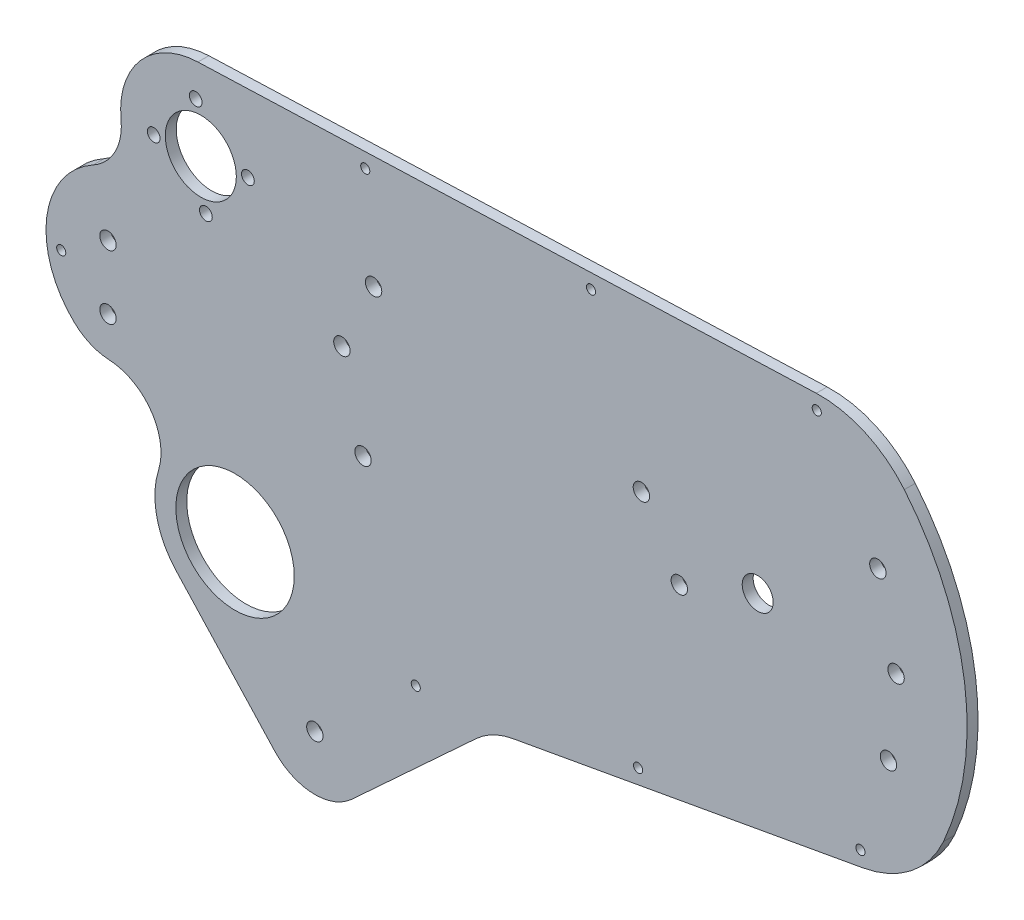
SolidWorks part; units mm, degrees
ref_plane "Front Plane" through (0, 0, 0) normal (0, 0, 1) x (1, 0, 0)
ref_plane "Top Plane" through (0, 0, 0) normal (0, 1, 0) x (1, 0, 0)
ref_plane "Right Plane" through (0, 0, 0) normal (1, 0, 0) x (0, 0, -1)
sketch "Sketch1" plane through (0, 0, 0) normal (0, 0, 1) x (1, 0, 0)
  line L0 (86.8854, -33.5) -> (-137.2004, -33.5) construction
  line L1 (-111.886, 49.4802) -> (83.0489, 41.2139) construction
  line L2 (-115.2069, 49.6211) -> (-101.035, -81.6153) construction
  line L3 (-97.8208, -80.7688) -> (92.1699, -30.731) construction
  line L4 (78.7977, 41.3942) -> (86.7407, -32.1609) construction
  line L5 (-108.121, -15.9971) -> (82.7692, 4.6166) construction
  line L6 (91, -33.5) -> (-88.5, -33.5) construction
  line L7 (-97.4673, 5.5) -> (-155.3054, 5.5) construction
  line L8 (-138.3, -14) -> (-155.3054, -14) construction
  line L9 (-138.3, 5.5) -> (-138.3, -33.5) construction
  line L10 (-155.3054, 5.5) -> (-155.3054, -33.5) construction
  line L11 (40.0178, 33.5) -> (40.0178, -33.5) construction
  line L12 (-101.0559, -81.4218) -> (-90.5433, -79.5278)
  line L13 (-91.5, 33.5) -> (88, 33.5) construction
  line L14 (-68.3, -21.5) -> (-107.0746, -25.6872) construction
  line L15 (-138.3, -5.25) -> (-81.5148, -93.5701) construction
  line L17 (-119.5948, -74.4106) -> (-92.5405, -103.7404)
  line L18 (-71.3446, -104.5958) -> (-37.2211, -73.1197)
  line L19 (-27.1401, -68.1042) -> (68.9251, -50.7959)
  line L20 (-115.1862, 49.4288) -> (56.0883, 55.6165)
  circle A0 centre (40.0178, 0) radius 4.25
  circle A1 centre (-112.8181, 27.5) radius 13 construction
  circle A2 centre (-103.4238, -59.4942) radius 13 construction
  arc A3 (-91.5, 33.5) -> (-88.5, -33.5) centre (-18.0922, 3.2198) ccw construction
  circle A4 centre (-68.3, -21.5) radius 2.25
  circle A6 centre (-138.3, -5.25) radius 2.25
  circle A7 centre (-138.3, -22.75) radius 2.25
  arc A8 (-142.3827, 10.6321) -> (-147.5429, -29.3643) centre (-130.3054, -11.2571) ccw
  arc A9 (-147.5429, -29.3643) -> (-137.2004, -33.5) centre (-137.2004, -18.5) ccw
  circle A10 centre (-112.8181, 27.5) radius 22
  arc A11 (68.9251, -50.7959) -> (91, -33.5) centre (63.6055, -21.2712) ccw
  circle A12 centre (-103.4238, -59.4942) radius 22
  arc A13 (91, -33.5) -> (80.2612, 44.7896) centre (22.6589, -2.9929) ccw
  arc A14 (91, -33.5) -> (88, 33.5) centre (22.6589, -2.9929) ccw construction
  arc A17 (-124.4228, -52.9336) -> (-137.9704, -33.4802) centre (-138.7403, -48.4604) ccw
  arc A18 (-142.3827, 10.6321) -> (-134.7058, 25.2795) centre (-149.6292, 23.7656) ccw
  circle A19 centre (-74.1, 1.7) radius 2.25
  circle A20 centre (-65.4, 20.2) radius 2.25
  circle A21 centre (8.1, 8.2) radius 2.25
  circle A23 centre (18.5, -8.7) radius 2.25
  circle A25 centre (78, -0.1) radius 2.25
  circle A26 centre (75.9, -21.8) radius 2.25
  circle A27 centre (73, 22.4) radius 2.25
  arc A28 (80.2612, 44.7896) -> (56.0883, 55.6165) centre (57.1714, 25.636) ccw
  circle A30 centre (-81.5148, -93.5701) radius 2.25
  circle A36 centre (-114.2138, 40.4249) radius 1.75
  circle A37 centre (-99.8933, 28.8957) radius 1.75
  circle A38 centre (-111.4224, 14.5751) radius 1.75
  circle A39 centre (-125.743, 26.1043) radius 1.75
  circle A40 centre (-104.8196, -46.5694) radius 1.75
  circle A41 centre (-90.499, -58.0985) radius 1.75
  circle A42 centre (-102.0281, -72.4191) radius 1.75
  circle A43 centre (-116.3487, -60.89) radius 1.75
  circle A44 centre (40.0178, 0) radius 35 construction
  circle A45 centre (40.0178, 0) radius 43
  circle A49 centre (-103.4238, -59.4942) radius 16.25
  circle A50 centre (-112.8181, 27.5) radius 16.25
  circle A51 centre (-112.8181, 27.5) radius 9.75
  circle A52 centre (-103.4238, -59.4942) radius 9.75
  arc A53 (91, -33.5) -> (88, 33.5) centre (22.6589, -2.9929) ccw construction
  arc A54 (-92.5405, -103.7404) -> (-71.3446, -104.5958) centre (-81.5148, -93.5701) ccw
  arc A55 (-27.1401, -68.1042) -> (-37.2211, -73.1197) centre (-23.5699, -87.9191) ccw
  circle A56 centre (-68.3, -21.5) radius 2.25 construction
  circle A57 centre (-74.1, 1.7) radius 2.25 construction
  circle A58 centre (-65.4, 20.2) radius 2.25 construction
  circle A59 centre (18.5, -8.7) radius 2.25 construction
  circle A60 centre (8.1, 8.2) radius 2.25 construction
  circle A61 centre (75.9, -21.8) radius 2.25 construction
  circle A62 centre (78, -0.1) radius 2.25 construction
  circle A63 centre (73, 22.4) radius 2.25 construction
  point P52 (82.7692, 4.6166)
  point P109 (-112.8181, 27.5)
  point P118 (-103.4238, -59.4942)
  dimension "D5" = 4.5
  dimension "D6" = 25
  dimension "D9" = 15
  dimension "D13" = 30
  dimension "D14" = 26
  dimension "D11" = 44
  dimension "D15" = 3.5
  dimension "D12" = 70
  dimension "D19" = 8.5
  dimension "D20" = 19.5
  dimension "D22" = 32.5
  dimension "D26" = 55
  dimension "D2" = 39
  dimension "D3" = 70
  dimension "D4" = 17.5
  dimension "D7" = 14
  dimension "D8" = 10
  dimension "D10" = 87.5
  dimension "D21" = 192
  dimension "D23" = 39
  dimension "D25" = 105
  dimension "D18" = 8
  dimension "D16" = 4
  dimension "D17" = 4
extrude "Boss-Extrude1" add sketch "Sketch1" along normal blind 3
sketch "Sketch2" plane through (0, 0, 3) normal (0, 0, 1) x (1, 0, 0)
  line L0 (68.2158, -46.8592) -> (7.1983, -57.8529) construction
  line L1 (-138.3, -5.25) -> (-138.3, -22.75) construction
  line L2 (7.1983, -57.8529) -> (-53.8193, -68.8467) construction
  line L7 (56.2327, 51.6191) -> (-113.468, 45.4883)
  line L8 (56.2327, 51.6191) -> (-113.468, 45.4883)
  line L9 (-67.6865, 47.1422) -> (-5.7269, 49.3806) construction
  line L10 (-5.7269, 49.3806) -> (56.2327, 51.6191) construction
  line L13 (-116.6546, -71.6986) -> (-89.6003, -101.0283)
  line L14 (-74.0566, -101.6556) -> (-39.9332, -70.1796)
  line L15 (-27.8493, -64.1676) -> (68.2158, -46.8592)
  line L17 (-116.6546, -71.6986) -> (-89.6003, -101.0283) construction
  line L18 (-74.0566, -101.6556) -> (-39.9332, -70.1796) construction
  line L19 (-109.9557, -78.9609) -> (68.2158, -46.8592) construction
  circle A0 centre (7.1983, -57.8529) radius 1.25
  circle A2 centre (-53.8193, -68.8467) radius 1.25
  arc A14 (77.1825, 42.2358) -> (56.2327, 51.6191) centre (57.1714, 25.636) ccw
  arc A15 (77.1825, 42.2358) -> (56.2327, 51.6191) centre (57.1714, 25.636) ccw
  arc A16 (68.2158, -46.8592) -> (87.3474, -31.8695) centre (63.6055, -21.2712) ccw
  arc A17 (-114.0495, -74.5228) -> (-104.0135, -77.8903) centre (-105.964, -67.0646) ccw construction
  circle A21 centre (68.2158, -46.8592) radius 1.25
  circle A23 centre (56.2327, 51.6191) radius 1.25
  circle A24 centre (-5.7269, 49.3806) radius 1.25
  circle A27 centre (-67.6865, 47.1422) radius 1.25
  arc A28 (-113.468, 45.4883) -> (-130.7262, 25.6832) centre (-112.8181, 27.5) ccw
  arc A29 (-140.4504, 7.1298) -> (-130.7262, 25.6832) centre (-149.6292, 23.7656) ccw
  arc A30 (-140.4504, 7.1298) -> (-144.7849, -26.4671) centre (-130.3054, -11.2571) ccw
  arc A31 (-144.7849, -26.4671) -> (-137.765, -29.4855) centre (-137.2004, -18.5) ccw
  arc A32 (-120.6048, -54.1264) -> (-137.765, -29.4855) centre (-138.7403, -48.4604) ccw
  arc A33 (-120.6048, -54.1264) -> (-116.6546, -71.6986) centre (-103.4238, -59.4942) ccw
  arc A34 (-89.6003, -101.0283) -> (-74.0566, -101.6556) centre (-81.5148, -93.5701) ccw
  arc A35 (-27.8493, -64.1676) -> (-39.9332, -70.1796) centre (-23.5699, -87.9191) ccw
  arc A36 (87.3474, -31.8695) -> (77.1825, 42.2358) centre (22.6589, -2.9929) ccw
  arc A37 (-113.468, 45.4883) -> (-130.7262, 25.6832) centre (-112.8181, 27.5) ccw construction
  arc A38 (-140.4504, 7.1298) -> (-130.7262, 25.6832) centre (-149.6292, 23.7656) ccw construction
  arc A39 (-140.4504, 7.1298) -> (-144.7849, -26.4671) centre (-130.3054, -11.2571) ccw construction
  arc A40 (-144.7849, -26.4671) -> (-137.765, -29.4855) centre (-137.2004, -18.5) ccw construction
  arc A41 (-120.6048, -54.1264) -> (-137.765, -29.4855) centre (-138.7403, -48.4604) ccw construction
  arc A42 (-120.6048, -54.1264) -> (-116.6546, -71.6986) centre (-103.4238, -59.4942) ccw construction
  arc A43 (-89.6003, -101.0283) -> (-74.0566, -101.6556) centre (-81.5148, -93.5701) ccw construction
  arc A44 (-27.8493, -64.1676) -> (-39.9332, -70.1796) centre (-23.5699, -87.9191) ccw construction
  arc A45 (87.3474, -31.8695) -> (77.1825, 42.2358) centre (22.6589, -2.9929) ccw construction
  circle A47 centre (-151.1255, -14) radius 1.25
  arc A51 (68.2158, -46.8592) -> (87.3474, -31.8695) centre (63.6055, -21.2712) ccw
  point P2 (-138.3, -14)
  dimension "D4" = 2.5
  dimension "D2" = 62
  dimension "D1" = 4
extrude "Cut-Extrude1" cut sketch "Sketch2" against normal through all
